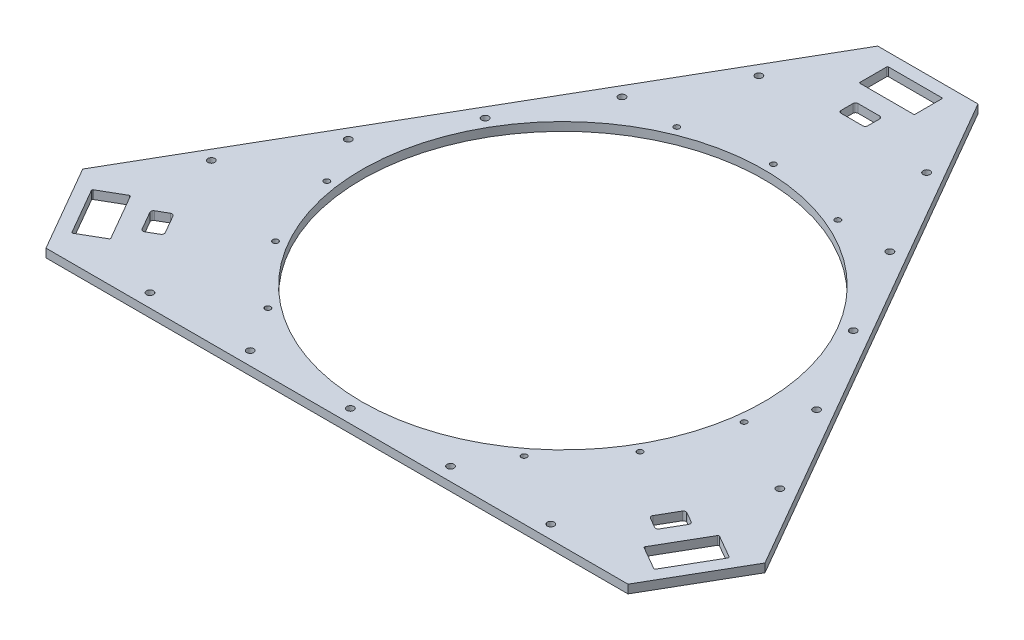
SolidWorks part; units mm, degrees
material "6061-T6 (SS)"
ref_plane "Front Plane" through (0, 0, 0) normal (0, 0, 1) x (1, 0, 0)
ref_plane "Top Plane" through (0, 0, 0) normal (0, 1, 0) x (1, 0, 0)
ref_plane "Right Plane" through (0, 0, 0) normal (1, 0, 0) x (0, 0, -1)
sketch "Sketch1" plane through (-388.2817, 0, -288.1857) normal (0, 1, 0) x (1, 0, 0)
  line L0 (1747.5708, -13084.8246) -> (1672.5144, -13084.8246)
  line L1 (1672.5144, -13084.8246) -> (1454.7035, -13462.0841)
  line L2 (1454.7035, -13462.0841) -> (1492.2317, -13527.0849)
  line L3 (1492.2317, -13527.0849) -> (1927.8535, -13527.0849)
  line L4 (1927.8535, -13527.0849) -> (1965.3817, -13462.0841)
  line L5 (1965.3817, -13462.0841) -> (1747.5708, -13084.8246)
  line L9 (1681.81, -13068.724) -> (1641.3158, -13138.8621) construction
  line L11 (1548.8311, -13527.0849) -> (1464.0303, -13527.0849) construction
  line L14 (1978.4206, -13484.668) -> (1947.1007, -13430.4205) construction
  line L64 (1710.0426, -13357.9978) -> (1856.4763, -13273.4543) construction
  line L65 (1710.0426, -13357.9978) -> (1710.0426, -13527.0849) construction
  line L66 (1710.0426, -13357.9978) -> (1563.6089, -13273.4543) construction
  line L68 (1730.6926, -13114.8746) -> (1730.6926, -13095.0746)
  line L69 (1729.9426, -13094.3246) -> (1690.1426, -13094.3246)
  line L70 (1690.1426, -13115.6246) -> (1729.9426, -13115.6246)
  line L71 (1689.3926, -13095.0746) -> (1689.3926, -13114.8746)
  line L98 (1492.6694, -13507.3429) -> (1509.8167, -13497.4429)
  line L99 (1510.0912, -13496.4184) -> (1490.1912, -13461.9506)
  line L100 (1471.7449, -13472.6006) -> (1491.6448, -13507.0684)
  line L101 (1489.1667, -13461.6761) -> (1472.0194, -13471.5761)
  line L126 (1948.0658, -13471.5761) -> (1930.9185, -13461.6761)
  line L127 (1910.2685, -13497.4429) -> (1927.4158, -13507.3429)
  line L128 (1928.4403, -13507.0684) -> (1948.3403, -13472.6006)
  line L129 (1929.894, -13461.9506) -> (1909.994, -13496.4184)
  circle A19 centre (1710.0426, -13357.9978) radius 150.5
  arc A23 (1729.9426, -13115.6246) -> (1730.6926, -13114.8746) centre (1729.9426, -13114.8746) ccw
  arc A24 (1730.6926, -13095.0746) -> (1729.9426, -13094.3246) centre (1729.9426, -13095.0746) ccw
  arc A25 (1690.1426, -13094.3246) -> (1689.3926, -13095.0746) centre (1690.1426, -13095.0746) ccw
  arc A26 (1689.3926, -13114.8746) -> (1690.1426, -13115.6246) centre (1690.1426, -13114.8746) ccw
  arc A45 (1509.8167, -13497.4429) -> (1510.0912, -13496.4184) centre (1509.4417, -13496.7934) ccw
  arc A46 (1491.6448, -13507.0684) -> (1492.6694, -13507.3429) centre (1492.2944, -13506.6934) ccw
  arc A47 (1490.1912, -13461.9506) -> (1489.1667, -13461.6761) centre (1489.5417, -13462.3256) ccw
  arc A48 (1472.0194, -13471.5761) -> (1471.7449, -13472.6006) centre (1472.3944, -13472.2256) ccw
  arc A53 (1927.4158, -13507.3429) -> (1928.4403, -13507.0684) centre (1927.7908, -13506.6934) ccw
  arc A59 (1948.3403, -13472.6006) -> (1948.0658, -13471.5761) centre (1947.6908, -13472.2256) ccw
  arc A60 (1930.9185, -13461.6761) -> (1929.894, -13461.9506) centre (1930.5435, -13462.3256) ccw
  arc A61 (1909.994, -13496.4184) -> (1910.2685, -13497.4429) centre (1910.6435, -13496.7934) ccw
  point P5 (0, 0)
  dimension "D1" = 301
extrude "Boss-Extrude1" add sketch "Sketch1" along normal blind 6.35
sketch "Sketch3" plane through (0, 6.35, 0) normal (0, 1, 0) x (1, 0, 0)
  line L0 (1284.2326, -12796.6389) -> (1066.4218, -13173.8984) construction
  line L1 (1175.3272, -12985.2687) -> (1188.9457, -12993.1313) construction
  circle A0 centre (1183.9875, -12990.2687) radius 2.6
  circle A1 centre (1146.4875, -13055.2206) radius 2.6
  circle A2 centre (1108.9875, -13120.1725) radius 2.6
  circle A3 centre (1221.4875, -12925.3168) radius 2.6
  circle A4 centre (1258.9875, -12860.3649) radius 2.6
  circle A5 centre (1459.5343, -12990.2687) radius 2.6
  circle A6 centre (1497.0343, -13055.2206) radius 2.6
  circle A7 centre (1534.5343, -13120.1725) radius 2.6
  circle A8 centre (1422.0343, -12925.3168) radius 2.6
  circle A9 centre (1384.5343, -12860.3649) radius 2.6
  circle A10 centre (1321.7609, -13228.8992) radius 2.6
  circle A11 centre (1246.7609, -13228.8992) radius 2.6
  circle A12 centre (1171.7609, -13228.8992) radius 2.6
  circle A13 centre (1396.7609, -13228.8992) radius 2.6
  circle A14 centre (1471.7609, -13228.8992) radius 2.6
  point P37 (1321.7609, -13069.8122)
  dimension "D1" = 5.2
  dimension "D2" = 10
  dimension "D3" = 3
  dimension "D4" = 3
  dimension "D5" = 3
extrude "Cut-Extrude2" cut sketch "Sketch3" against normal blind 10
hole_wizard "M5x0.8 Tapped Hole1" positions "Sketch7" profile "Sketch8" tap size "M5x0.8" standard "ANSI Metric" end condition through all
sketch "Sketch7" plane through (0, 6.35, 0) normal (0, 1, 0) x (1, 0, 0)
  line L0 (1321.7609, -12796.6389) -> (1321.7609, -13238.8992) construction
  line L1 (1359.2891, -12796.6389) -> (1284.2326, -12796.6389) construction
  line L2 (1103.95, -13238.8992) -> (1539.5717, -13238.8992) construction
  line L3 (1321.7609, -12912.3122) -> (1321.7609, -13069.8122) construction
  line L5 (1321.7609, -13069.8122) -> (1382.0335, -12924.3012) construction
  line L7 (1321.7609, -12912.3122) -> (1382.0335, -12924.3012) construction
  line L9 (1261.4882, -12924.3012) -> (1321.7609, -12912.3122) construction
  line L11 (1185.3619, -13148.5622) -> (1165.6083, -13090.3701) construction
  line L13 (1185.3619, -13148.5622) -> (1225.881, -13194.7653) construction
  line L15 (1458.1599, -13148.5622) -> (1477.9134, -13090.3701) construction
  line L17 (1458.1599, -13148.5622) -> (1417.6408, -13194.7653) construction
  line L19 (1085.1859, -13206.3988) -> (1321.7609, -13069.8122) construction
  line L20 (1066.4218, -13173.8984) -> (1103.95, -13238.8992) construction
  line L22 (1558.3359, -13206.3988) -> (1321.7609, -13069.8122) construction
  line L23 (1539.5717, -13238.8992) -> (1577.1, -13173.8984) construction
  circle A0 centre (1321.7609, -13069.8122) radius 150.5 construction
  circle A2 centre (1321.7609, -13069.8122) radius 157.5 construction
  point P0 (1321.7609, -12912.3122)
  point P13 (1321.7609, -13069.8122)
  point P23 (1382.0335, -12924.3012)
  point P25 (1261.4882, -12924.3012)
  point P27 (1185.3619, -13148.5622)
  point P29 (1165.6083, -13090.3701)
  point P31 (1225.881, -13194.7653)
  point P33 (1417.6408, -13194.7653)
  point P35 (1458.1599, -13148.5622)
  point P37 (1477.9134, -13090.3701)
  dimension "D1" = 157.5
  dimension "D2" = 22.5
sketch "Sketch8" plane through (1321.7609, 6.35, 12912.3122) normal (1, 0, 0) x (0, 0, 1)
  line L0 (0, 0) -> (0, 6.35)
  line L1 (0, 6.35) -> (2.1, 6.35)
  line L2 (2.1, 6.35) -> (2.1, 0)
  line L5 (2.1, 0) -> (0, 0)
  line L11 (0, -6.35) -> (0, 107.95) construction
  dimension "Thru Tap Drill Dia." = 4.2
  dimension "Thru Tap Drill Depth" = 6.35
cosmetic thread "Hole Thread1" parameters "D2"=5
cosmetic thread "Hole Thread2" parameters "D2"=5
cosmetic thread "Hole Thread3" parameters "D2"=5
cosmetic thread "Hole Thread4" parameters "D2"=5
cosmetic thread "Hole Thread5" parameters "D2"=5
cosmetic thread "Hole Thread6" parameters "D2"=5
cosmetic thread "Hole Thread7" parameters "D2"=5
cosmetic thread "Hole Thread8" parameters "D2"=5
cosmetic thread "Hole Thread9" parameters "D2"=5
sketch "Sketch9" plane through (0, 6.35, 0) normal (0, 1, 0) x (1, 0, 0)
  line L0 (1312.2013, -12841.2389) -> (1332.2013, -12841.2389) construction
  line L1 (1522.7589, -13174.82) -> (1515.2244, -13170.47)
  line L2 (1301.8609, -12827.4389) -> (1341.6609, -12827.4389) construction
  line L3 (1312.2013, -12843.2389) -> (1312.2013, -12851.9389)
  line L4 (1332.2013, -12843.2389) -> (1332.2013, -12851.9389)
  line L5 (1314.2013, -12853.9389) -> (1330.2013, -12853.9389)
  line L6 (1314.2013, -12841.2389) -> (1330.2013, -12841.2389)
  line L7 (1512.7589, -13192.1405) -> (1505.2244, -13187.7905)
  line L8 (1512.4924, -13171.2021) -> (1504.4924, -13185.0585)
  line L9 (1523.4909, -13177.5521) -> (1515.4909, -13191.4085)
  line L10 (1524.4909, -13175.82) -> (1514.4909, -13193.1405) construction
  line L11 (1130.3224, -13191.3776) -> (1137.8569, -13187.0276)
  line L12 (1120.3224, -13174.0571) -> (1127.8569, -13169.7071)
  line L13 (1138.5889, -13184.2956) -> (1130.5889, -13170.4392)
  line L14 (1127.5904, -13190.6456) -> (1119.5904, -13176.7892)
  line L15 (1128.5904, -13192.3776) -> (1118.5904, -13175.0571) construction
  arc A0 (1332.2013, -12851.9389) -> (1330.2013, -12853.9389) centre (1330.2013, -12851.9389) cw
  arc A1 (1312.2013, -12851.9389) -> (1314.2013, -12853.9389) centre (1314.2013, -12851.9389) ccw
  arc A2 (1312.2013, -12843.2389) -> (1314.2013, -12841.2389) centre (1314.2013, -12843.2389) cw
  arc A3 (1332.2013, -12843.2389) -> (1330.2013, -12841.2389) centre (1330.2013, -12843.2389) ccw
  arc A4 (1505.2244, -13187.7905) -> (1504.4924, -13185.0585) centre (1506.2244, -13186.0585) cw
  arc A5 (1515.2244, -13170.47) -> (1512.4924, -13171.2021) centre (1514.2244, -13172.2021) ccw
  arc A6 (1522.7589, -13174.82) -> (1523.4909, -13177.5521) centre (1521.7589, -13176.5521) cw
  arc A7 (1512.7589, -13192.1405) -> (1515.4909, -13191.4085) centre (1513.7589, -13190.4085) ccw
  arc A8 (1127.8569, -13169.7071) -> (1130.5889, -13170.4392) centre (1128.8569, -13171.4392) cw
  arc A9 (1137.8569, -13187.0276) -> (1138.5889, -13184.2956) centre (1136.8569, -13185.2956) ccw
  arc A10 (1130.3224, -13191.3776) -> (1127.5904, -13190.6456) centre (1129.3224, -13189.6456) cw
  arc A11 (1120.3224, -13174.0571) -> (1119.5904, -13176.7892) centre (1121.3224, -13175.7892) ccw
  point P5 (1322.2013, -12841.2389)
  point P24 (1519.4909, -13184.4803)
  point P33 (1321.7609, -13069.8122)
  point P40 (1123.5904, -13183.7174)
  point P52 (1321.7609, -13069.8122)
  dimension "D3" = 2
  dimension "D5" = 2
  dimension "D1" = 20
  dimension "D2" = 12.7
  dimension "D4" = 26.5
  dimension "D6" = 3
extrude "Cut-Extrude3" cut sketch "Sketch9" against normal blind 10
